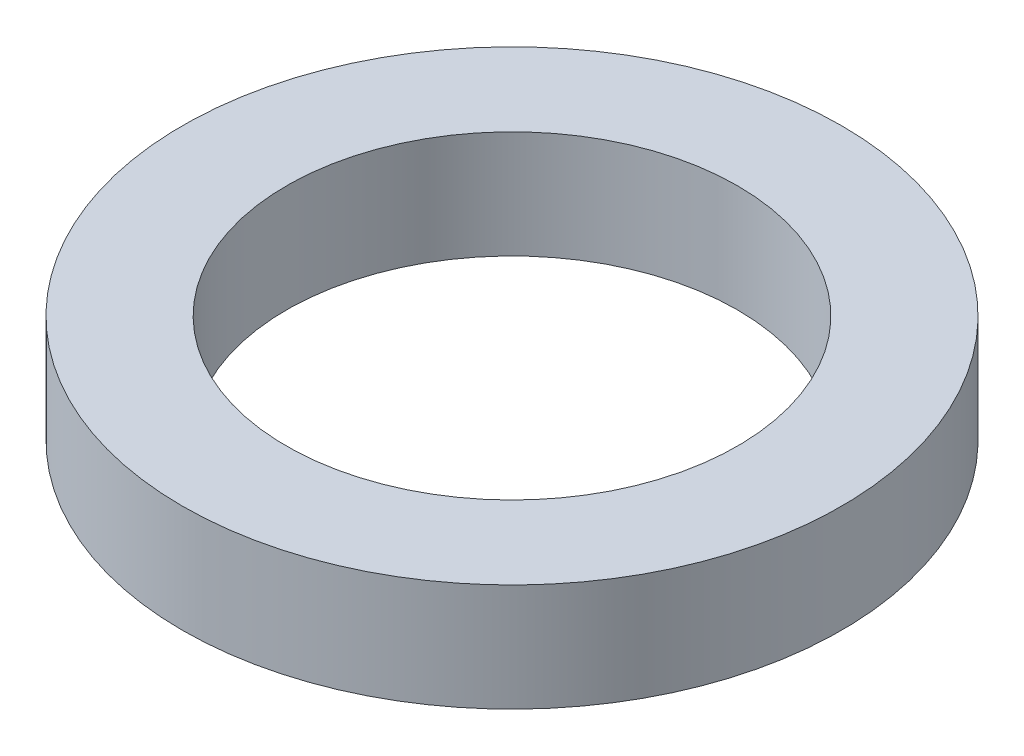
SolidWorks part; units mm, degrees
ref_plane "前视基准面" through (0, 0, 0) normal (0, 0, 1) x (1, 0, 0)
ref_plane "上视基准面" through (0, 0, 0) normal (0, 1, 0) x (1, 0, 0)
ref_plane "右视基准面" through (0, 0, 0) normal (1, 0, 0) x (0, 0, -1)
sketch "草图1" plane through (0, 0, 0) normal (0, 1, 0) x (1, 0, 0)
  circle A0 centre (0, 0) radius 6.5
  circle A1 centre (0, 0) radius 9.5
  dimension "D1" = 13
  dimension "D2" = 19
extrude "凸台-拉伸1" add sketch "草图1" along normal blind 3.1
